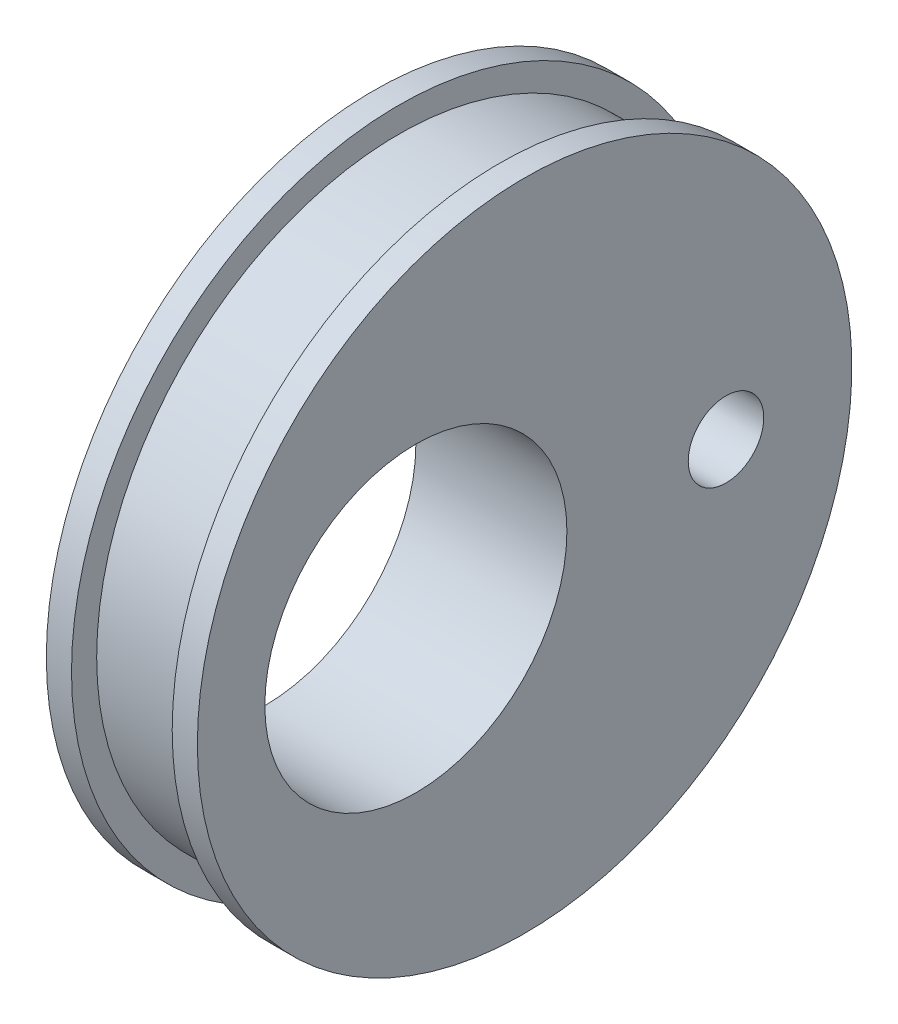
SolidWorks part; units mm, degrees
ref_plane "Front Plane" through (0, 0, 0) normal (0, 0, 1) x (1, 0, 0)
ref_plane "Top Plane" through (0, 0, 0) normal (0, 1, 0) x (1, 0, 0)
ref_plane "Right Plane" through (0, 0, 0) normal (1, 0, 0) x (0, 0, -1)
sketch "Sketch2" plane through (0, 0, 0) normal (0, 0, 1) x (1, 0, 0)
  line L0 (0, 0) -> (0, 19.05)
  line L1 (0, 19.05) -> (0, 20.6375)
  line L2 (0, 20.6375) -> (1.5875, 20.6375)
  line L3 (1.5875, 20.6375) -> (1.5875, 19.05)
  line L4 (1.5875, 19.05) -> (7.9375, 19.05)
  line L5 (4.7625, 19.05) -> (4.7625, 2.0687) construction
  line L6 (9.525, 0) -> (9.525, 19.05)
  line L7 (7.9375, 20.6375) -> (7.9375, 19.05)
  line L8 (9.525, 20.6375) -> (7.9375, 20.6375)
  line L9 (9.525, 19.05) -> (9.525, 20.6375)
  line L10 (0, 0) -> (9.525, 0)
revolve "Revolve1" add sketch "Sketch2" angle 360 about L10
sketch "Sketch3" plane through (0, 0, 0) normal (-1, 0, 0) x (0, 0, 1)
  circle A0 centre (-12.7, 0) radius 2.3813
  circle A1 centre (6.858, 0) radius 9.525
  dimension "D1" = 12.7
  dimension "D3" = 19.05
  dimension "D2" = 6.858
extrude "Cut-Extrude1" cut sketch "Sketch3" against normal through all
